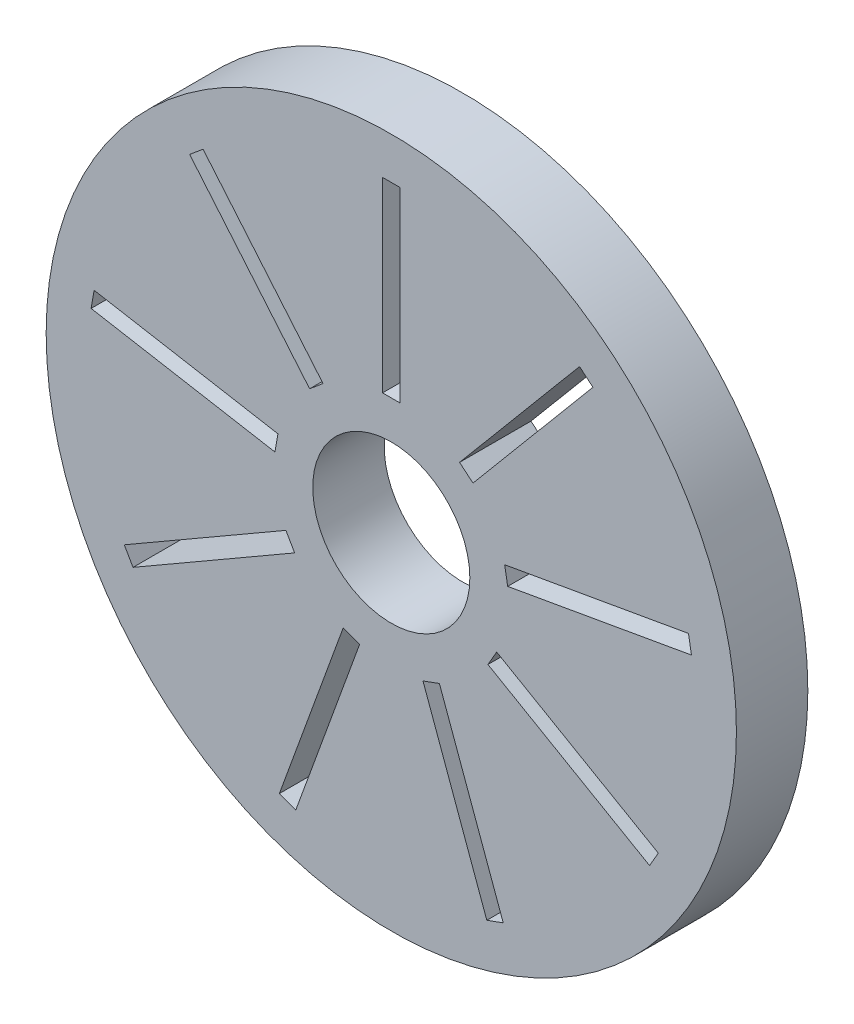
SolidWorks part; units mm, degrees
ref_plane "前视基准面" through (0, 0, 0) normal (0, 0, 1) x (1, 0, 0)
ref_plane "上视基准面" through (0, 0, 0) normal (0, 1, 0) x (1, 0, 0)
ref_plane "右视基准面" through (0, 0, 0) normal (1, 0, 0) x (0, 0, -1)
sketch "草图1" plane through (0, 0, 0) normal (0, 0, 1) x (1, 0, 0)
  circle A9 centre (0, 0) radius 29
  point P35 (0, 0)
  dimension "D2" = 58
extrude "凸台-拉伸1" add sketch "草图1" along normal blind 6
sketch "草图2" plane through (0, 0, 6) normal (0, 0, 1) x (1, 0, 0)
  circle A0 centre (0, 0) radius 6.6
  dimension "D1" = 13.2
extrude "切除-拉伸1" cut sketch "草图2" against normal through all
sketch "草图3" plane through (0, 0, 6) normal (0, 0, 1) x (1, 0, 0)
  line L0 (15.8164, 19.9928) -> (5.7367, 7.9803)
  line L1 (-0.7351, 25.482) -> (0.7351, 25.482)
  line L2 (-0.7351, 25.482) -> (-0.7351, 9.8008)
  line L3 (-0.7351, 9.8008) -> (0.7351, 9.8008)
  line L4 (0.7351, 25.482) -> (0.7351, 9.8008)
  line L5 (-0.7351, 25.482) -> (0.7351, 9.8008) construction
  line L6 (-0.7351, 9.8008) -> (0.7351, 25.482) construction
  line L7 (15.8164, 19.9928) -> (16.9426, 19.0478)
  line L8 (16.9426, 19.0478) -> (6.8629, 7.0353)
  line L9 (5.7367, 7.9803) -> (6.8629, 7.0353)
  line L10 (24.9672, 5.1488) -> (9.5242, 2.4258)
  line L11 (24.9672, 5.1488) -> (25.2225, 3.701)
  line L12 (25.2225, 3.701) -> (9.7795, 0.978)
  line L13 (9.5242, 2.4258) -> (9.7795, 0.978)
  line L14 (22.4356, -12.1044) -> (8.8552, -4.2638)
  line L15 (22.4356, -12.1044) -> (21.7005, -13.3776)
  line L16 (21.7005, -13.3776) -> (8.1202, -5.537)
  line L17 (8.8552, -4.2638) -> (8.1202, -5.537)
  line L18 (9.4061, -23.6938) -> (4.0428, -8.9583)
  line L19 (9.4061, -23.6938) -> (8.0246, -24.1966)
  line L20 (8.0246, -24.1966) -> (2.6613, -9.4611)
  line L21 (4.0428, -8.9583) -> (2.6613, -9.4611)
  line L22 (-8.0246, -24.1966) -> (-2.6613, -9.4611)
  line L23 (-8.0246, -24.1966) -> (-9.4061, -23.6938)
  line L24 (-9.4061, -23.6938) -> (-4.0428, -8.9583)
  line L25 (-2.6613, -9.4611) -> (-4.0428, -8.9583)
  line L26 (-21.7005, -13.3776) -> (-8.1202, -5.537)
  line L27 (-21.7005, -13.3776) -> (-22.4356, -12.1044)
  line L28 (-22.4356, -12.1044) -> (-8.8552, -4.2638)
  line L29 (-8.1202, -5.537) -> (-8.8552, -4.2638)
  line L30 (-25.2225, 3.701) -> (-9.7795, 0.978)
  line L31 (-25.2225, 3.701) -> (-24.9672, 5.1488)
  line L32 (-24.9672, 5.1488) -> (-9.5242, 2.4258)
  line L33 (-9.7795, 0.978) -> (-9.5242, 2.4258)
  line L34 (-16.9426, 19.0478) -> (-6.8629, 7.0353)
  line L35 (-16.9426, 19.0478) -> (-15.8164, 19.9928)
  line L36 (-15.8164, 19.9928) -> (-5.7367, 7.9803)
  line L37 (-6.8629, 7.0353) -> (-5.7367, 7.9803)
  point P0 (0, 17.6414)
  point P40 (0, 0)
  dimension "D1" = 9
extrude "切除-拉伸2" cut sketch "草图3" against normal through all
